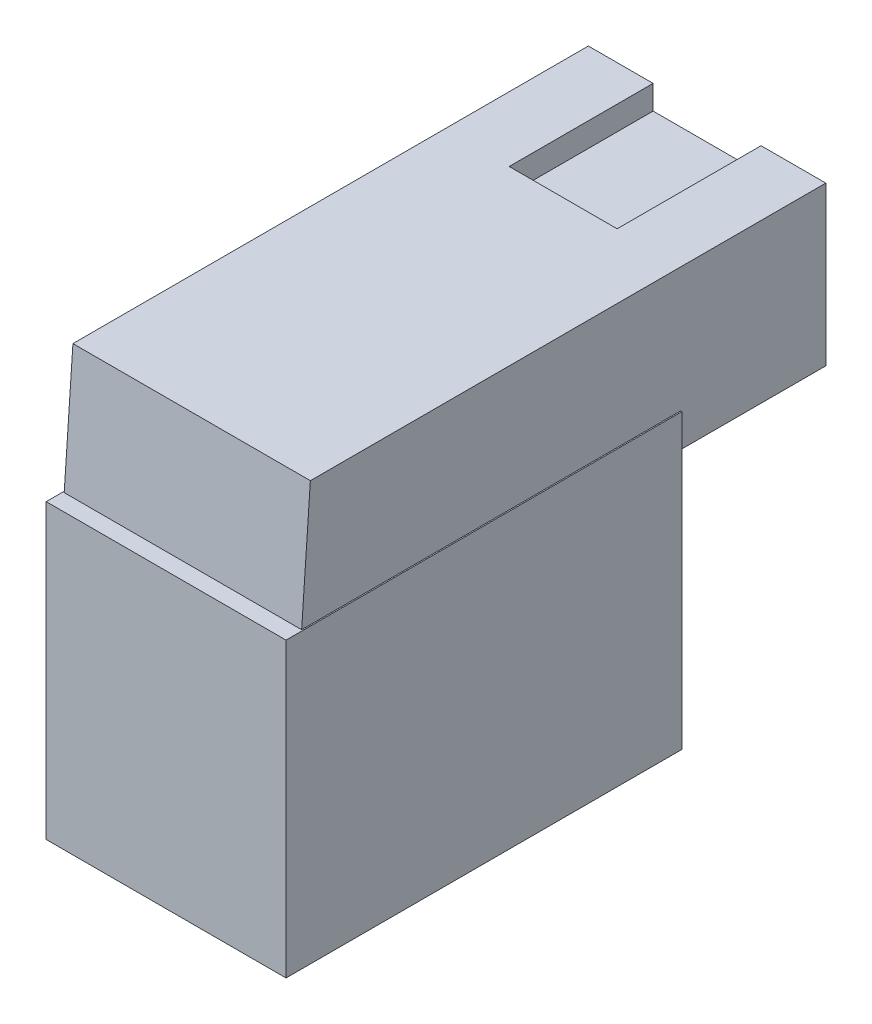
SolidWorks part; units mm, degrees
ref_plane "Front Plane" through (0, 0, 0) normal (0, 0, 1) x (1, 0, 0)
ref_plane "Top Plane" through (0, 0, 0) normal (0, 1, 0) x (1, 0, 0)
ref_plane "Right Plane" through (0, 0, 0) normal (1, 0, 0) x (0, 0, -1)
sketch "Sketch1" plane through (0, 0, 0) normal (0, 1, 0) x (1, 0, 0)
  line L1 (-5, 0) -> (5, 0)
  line L2 (-5, 0) -> (-5, 16.5)
  line L3 (-5, 16.5) -> (5, 16.5)
  line L4 (5, 0) -> (5, 16.5)
  dimension "D1" = 10
  dimension "D2" = 16.5
extrude "Main_Body" add sketch "Sketch1" along normal blind 12.2
sketch "Sketch2" plane through (0, 0, 0) normal (1, 0, 0) x (0, 0, -1)
  line L0 (0.65, 12.2) -> (16.45, 12.2)
  line L1 (0, 12.2) -> (16.5, 12.2) construction
  line L2 (16.45, 12.2) -> (16.45, 16.3)
  line L3 (16.45, 16.3) -> (0.9367, 16.3)
  line L4 (0.9367, 16.3) -> (0.65, 12.2)
  line L5 (16.5, 12.2) -> (16.5, 0) construction
  dimension "D1" = 0.05
  dimension "D2" = 4.1
  dimension "D3" = 15.8
  dimension "D4" = 86
extrude "G,H,L_Body" [suppressed] add sketch "Sketch2" along normal mid plane 9.9
sketch "Sketch3" [suppressed] plane through (0, 16.3, 0) normal (0, 1, 0) x (1, 0, 0)
  line L0 (0, 2.2967) -> (0, 5.7167) construction
  line L1 (-3, 5.7167) -> (3, 5.7167)
  line L2 (-3, 5.7167) -> (-3, 2.2967)
  line L3 (-3, 2.2967) -> (3, 2.2967)
  line L4 (3, 5.7167) -> (3, 2.2967)
  line L5 (4.95, 0.9367) -> (-4.95, 0.9367) construction
  dimension "D1" = 1.36
  dimension "D2" = 6
  dimension "D3" = 3.42
extrude "G,H_Base" [suppressed] add sketch "Sketch3" along normal blind 0.8 draft 15
sketch "Sketch4" [suppressed] plane through (0, 17.1, 0) normal (0, 1, 0) x (1, 0, 0)
  line L0 (-1.3, 4.1) -> (1.3, 4.1) construction
  line L2 (0, 0) -> (0, 4.1) construction
  circle A0 centre (-1.3, 4.1) radius 0.75
  circle A1 centre (1.3, 4.1) radius 0.75
  dimension "D1" = 1.5
  dimension "D2" = 2.6
  dimension "D3" = 4.1
extrude "G,H_Wires_1" [suppressed] add sketch "Sketch4" along normal blind 10
sketch "Sketch6" [suppressed] plane through (0, 27.1, 0) normal (0, 1, 0) x (1, 0, 0)
  circle A0 centre (-1.3, 4.1) radius 0.5
  circle A1 centre (1.3, 4.1) radius 0.5
  dimension "D1" = 1
extrude "G,H_Wires_2" [suppressed] add sketch "Sketch6" along normal blind 2
sketch "Sketch5" [suppressed] plane through (0, 16.3, 0) normal (0, 1, 0) x (1, 0, 0)
  line L0 (-1.3, 4.1) -> (-1.3, 6.7167) construction
  line L1 (-2.05, 7.0167) -> (-0.55, 7.0167)
  line L2 (-2.05, 7.0167) -> (-2.05, 6.7167)
  line L3 (-2.05, 6.7167) -> (-0.55, 6.7167)
  line L4 (-0.55, 7.0167) -> (-0.55, 6.7167)
  line L5 (0.55, 7.0167) -> (1.15, 7.0167)
  line L6 (0.55, 7.0167) -> (0.55, 6.7167)
  line L7 (0.55, 6.7167) -> (1.15, 6.7167)
  line L8 (2.05, 7.0167) -> (2.05, 6.7167)
  line L9 (1.15, 7.6167) -> (1.45, 7.6167)
  line L10 (1.15, 7.6167) -> (1.15, 7.0167)
  line L11 (1.15, 6.1167) -> (1.45, 6.1167)
  line L12 (1.45, 7.6167) -> (1.45, 7.0167)
  line L13 (1.3, 4.1) -> (1.3, 6.1167) construction
  line L14 (3, 5.7167) -> (-3, 5.7167) construction
  line L15 (1.45, 6.7167) -> (2.05, 6.7167)
  line L16 (1.15, 6.7167) -> (1.15, 6.1167)
  line L17 (1.45, 7.0167) -> (2.05, 7.0167)
  line L18 (1.45, 6.7167) -> (1.45, 6.1167)
  dimension "D1" = 0.3
  dimension "D2" = 1.5
  dimension "D3" = 1.5
  dimension "D4" = 0.6
  dimension "D5" = 0.6
  dimension "D6" = 1
extrude "G,H_Signs" [suppressed] add sketch "Sketch5" along normal blind 0.1
sketch "Sketch7" [suppressed] plane through (0, 16.3, 0) normal (0, 1, 0) x (1, 0, 0)
  line L0 (4.95, 16.45) -> (-4.95, 16.45) construction
  line L1 (-2, 16.45) -> (2, 16.45)
  line L2 (-2, 16.45) -> (-2, 10.85)
  line L3 (-2, 10.85) -> (2, 10.85)
  line L4 (2, 16.45) -> (2, 10.85)
  line L5 (0, 10.85) -> (0, 0) construction
  dimension "D1" = 4
  dimension "D2" = 5.6
extrude "G,H_Cut_1" [suppressed] cut sketch "Sketch7" against normal blind 0.1
chamfer "G,H_Cut_2" [suppressed] distance 1 angle 45
sketch "Sketch8" [suppressed] plane through (0, 0, 0) normal (1, 0, 0) x (0, 0, -1)
  line L0 (0.9367, 16.3) -> (7.1167, 16.3)
  line L1 (16.45, 16.3) -> (0.9367, 16.3) construction
  line L2 (7.1167, 16.3) -> (7.1167, 21.1)
  line L3 (7.1167, 21.1) -> (1.2723, 21.1)
  line L4 (1.2723, 21.1) -> (0.9367, 16.3)
  line L6 (0.9367, 16.3) -> (0.65, 12.2) construction
  dimension "D1" = 6.18
  dimension "D2" = 4.8
extrude "L_Base" [suppressed] add sketch "Sketch8" along normal mid plane 8
sketch "Sketch9" [suppressed] plane through (0, 21.1, 0) normal (0, 1, 0) x (1, 0, 0)
  line L0 (4, 7.1167) -> (-4, 7.1167) construction
  line L1 (-2.25, 7.1167) -> (2.25, 7.1167)
  line L2 (-2.25, 7.1167) -> (-2.25, 6.1167)
  line L3 (-2.25, 6.1167) -> (2.25, 6.1167)
  line L4 (2.25, 7.1167) -> (2.25, 6.1167)
  line L5 (-3.45, 4.8167) -> (3.45, 4.8167)
  line L6 (3.45, 4.8167) -> (3.45, 3.3167)
  line L7 (3.45, 3.3167) -> (2.9, 3.3167)
  line L8 (2.9, 3.3167) -> (2.9, 1.6167)
  line L9 (2.9, 1.6167) -> (-2.9, 1.6167)
  line L10 (-2.9, 1.6167) -> (-2.9, 3.3167)
  line L11 (-2.9, 3.3167) -> (-3.45, 3.3167)
  line L12 (-3.45, 3.3167) -> (-3.45, 4.8167)
  line L13 (0, 0) -> (0, 1.6167) construction
  line L14 (0, 1.6167) -> (0, 4.8167) construction
  line L15 (0, 4.8167) -> (0, 6.1167) construction
  dimension "D1" = 4.5
  dimension "D2" = 1
  dimension "D3" = 6.9
  dimension "D4" = 1.5
  dimension "D5" = 1.3
  dimension "D6" = 0.55
  dimension "D7" = 1.7
extrude "LO_Cut_1" [suppressed] cut sketch "Sketch9" against normal blind 6
sketch "Sketch10" [suppressed] plane through (0, 15.1, 0) normal (0, 1, 0) x (1, 0, 0)
  line L0 (3.45, 4.8167) -> (-3.45, 4.8167) construction
  line L1 (-1.75, 4.0167) -> (-0.75, 4.0167)
  line L2 (-1.75, 4.0167) -> (-1.75, 3.0167)
  line L3 (-1.75, 3.0167) -> (-0.75, 3.0167)
  line L4 (-0.75, 4.0167) -> (-0.75, 3.0167)
  line L5 (0.75, 4.0167) -> (1.75, 4.0167)
  line L6 (0.75, 4.0167) -> (0.75, 3.0167)
  line L7 (0.75, 3.0167) -> (1.75, 3.0167)
  line L8 (1.75, 4.0167) -> (1.75, 3.0167)
  line L9 (-2.9, 3.3167) -> (-2.9, 1.6167) construction
  dimension "D1" = 1
  dimension "D2" = 0.8
  dimension "D3" = 1.15
  dimension "D4" = 1.5
extrude "LO_Pins" [suppressed] add sketch "Sketch10" along normal blind 4
sketch "Sketch11" plane through (0, 0, 0) normal (1, 0, 0) x (0, 0, -1)
  line L0 (0.7, 12.2) -> (1.0636, 17.4)
  line L1 (16.5, 12.2) -> (0, 12.2) construction
  line L2 (1.0636, 17.4) -> (22.5536, 17.4)
  line L3 (22.5536, 17.4) -> (22.5536, 10.8)
  line L4 (22.5536, 10.8) -> (16.5, 10.8)
  line L5 (16.5, 12.2) -> (16.5, 0) construction
  line L6 (16.5, 10.8) -> (16.5, 12.2)
  line L7 (16.5, 12.2) -> (0.7, 12.2)
  line L8 (0, 12.2) -> (0, 0) construction
  dimension "D1" = 5.2
  dimension "D2" = 0.7
  dimension "D3" = 86
  dimension "D4" = 21.49
  dimension "D5" = 6.6
extrude "M_Base" add sketch "Sketch11" along normal mid plane 9.9
sketch "Sketch12" plane through (0, 0, -22.5536) normal (0, 0, -1) x (-1, 0, 0)
  line L0 (-4.95, 17.4) -> (4.95, 17.4) construction
  line L1 (-2.25, 17.4) -> (2.25, 17.4)
  line L2 (-2.25, 17.4) -> (-2.25, 16.4)
  line L3 (-2.25, 16.4) -> (2.25, 16.4)
  line L4 (2.25, 17.4) -> (2.25, 16.4)
  line L5 (-3.45, 15.1) -> (3.45, 15.1)
  line L6 (3.45, 15.1) -> (3.45, 13.6)
  line L7 (3.45, 13.6) -> (2.9, 13.6)
  line L8 (2.9, 13.6) -> (2.9, 11.9)
  line L9 (2.9, 11.9) -> (-2.9, 11.9)
  line L10 (-2.9, 11.9) -> (-2.9, 13.6)
  line L11 (-2.9, 13.6) -> (-3.45, 13.6)
  line L12 (-3.45, 13.6) -> (-3.45, 15.1)
  line L13 (0, 0) -> (0, 11.9) construction
  line L14 (0, 11.9) -> (0, 15.1) construction
  line L15 (0, 15.1) -> (0, 16.4) construction
  dimension "D1" = 4.5
  dimension "D2" = 1
  dimension "D3" = 1.3
  dimension "D4" = 6.9
  dimension "D5" = 1.5
  dimension "D6" = 0.55
  dimension "D7" = 1.7
extrude "MO_Cut_1" cut sketch "Sketch12" against normal blind 6
sketch "Sketch13" plane through (0, 0, -16.5536) normal (0, 0, -1) x (-1, 0, 0)
  line L0 (3.45, 15.1) -> (-3.45, 15.1) construction
  line L1 (-1.75, 14.3) -> (-0.75, 14.3)
  line L2 (-1.75, 14.3) -> (-1.75, 13.3)
  line L3 (-1.75, 13.3) -> (-0.75, 13.3)
  line L4 (-0.75, 14.3) -> (-0.75, 13.3)
  line L5 (0.75, 14.3) -> (1.75, 14.3)
  line L6 (0.75, 14.3) -> (0.75, 13.3)
  line L7 (0.75, 13.3) -> (1.75, 13.3)
  line L8 (1.75, 14.3) -> (1.75, 13.3)
  line L9 (2.9, 11.9) -> (2.9, 13.6) construction
  dimension "D1" = 1
  dimension "D2" = 1.5
  dimension "D3" = 0.8
  dimension "D4" = 1.15
extrude "MO_Pins" add sketch "Sketch13" along normal blind 5
